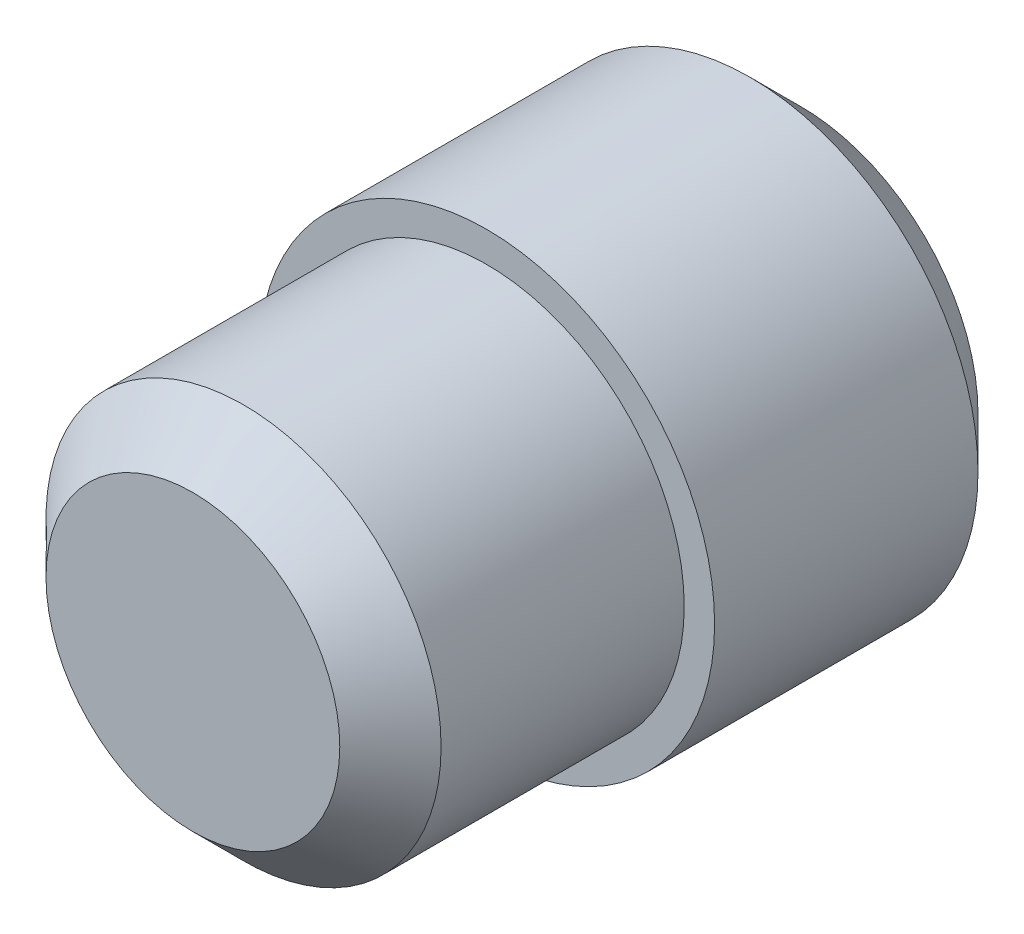
SolidWorks part; units mm, degrees
material "黄铜"
ref_plane "前视基准面" through (0, 0, 0) normal (0, 0, 1) x (1, 0, 0)
ref_plane "上视基准面" through (0, 0, 0) normal (0, 1, 0) x (1, 0, 0)
ref_plane "右视基准面" through (0, 0, 0) normal (1, 0, 0) x (0, 0, -1)
sketch "草图1" plane through (0, 0, 0) normal (0, 0, 1) x (1, 0, 0)
  circle A0 centre (0, 0) radius 2.25
  dimension "D1" = 4.5
extrude "拉伸1" add sketch "草图1" along normal blind 3.1
sketch "草图2" plane through (0, 0, 3.1) normal (0, 0, 1) x (1, 0, 0)
  circle A0 centre (0, 0) radius 1.95
  dimension "D1" = 3.9
extrude "拉伸2" add sketch "草图2" along normal blind 2.9
chamfer "倒角1" distance 0.5 angle 45 2 edges at (2.25, 0, 0) (1.95, 0, 6)
